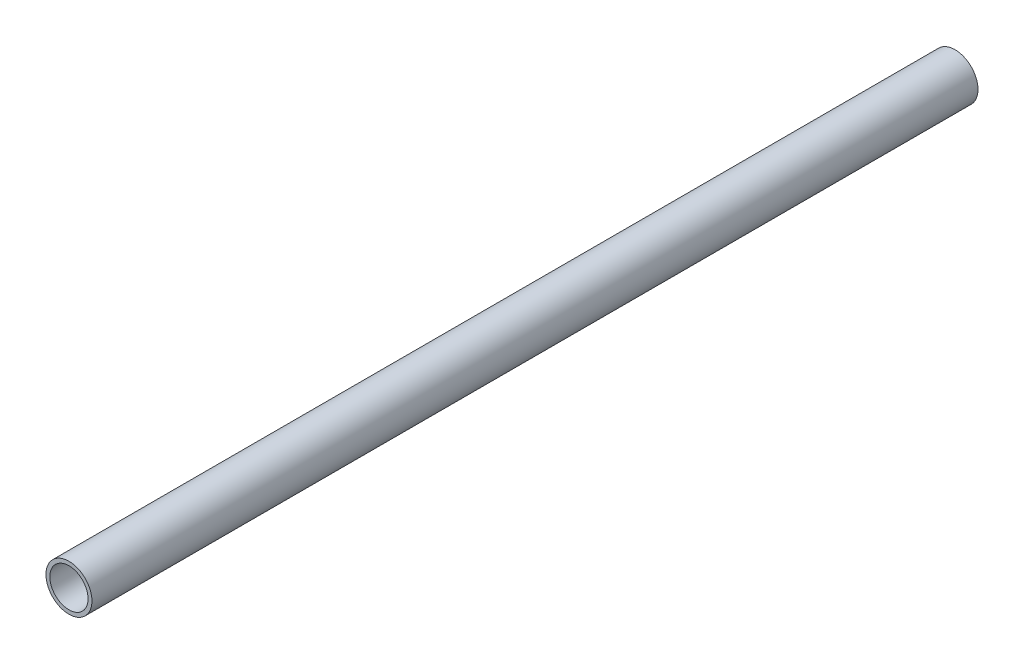
SolidWorks part; units mm, degrees
material "6061 Alloy"
ref_plane "Front Plane" through (0, 0, 0) normal (0, 0, 1) x (1, 0, 0)
ref_plane "Top Plane" through (0, 0, 0) normal (0, 1, 0) x (1, 0, 0)
ref_plane "Right Plane" through (0, 0, 0) normal (1, 0, 0) x (0, 0, -1)
sketch "Sketch1" plane through (0, 0, 0) normal (0, 0, 1) x (1, 0, 0)
  circle A0 centre (0, 0) radius 17.526
  circle A1 centre (0, 0) radius 21.082
  dimension "D1" = 42.164
  dimension "D2" = 35.052
extrude "Boss-Extrude1" add sketch "Sketch1" against normal blind 812.8
